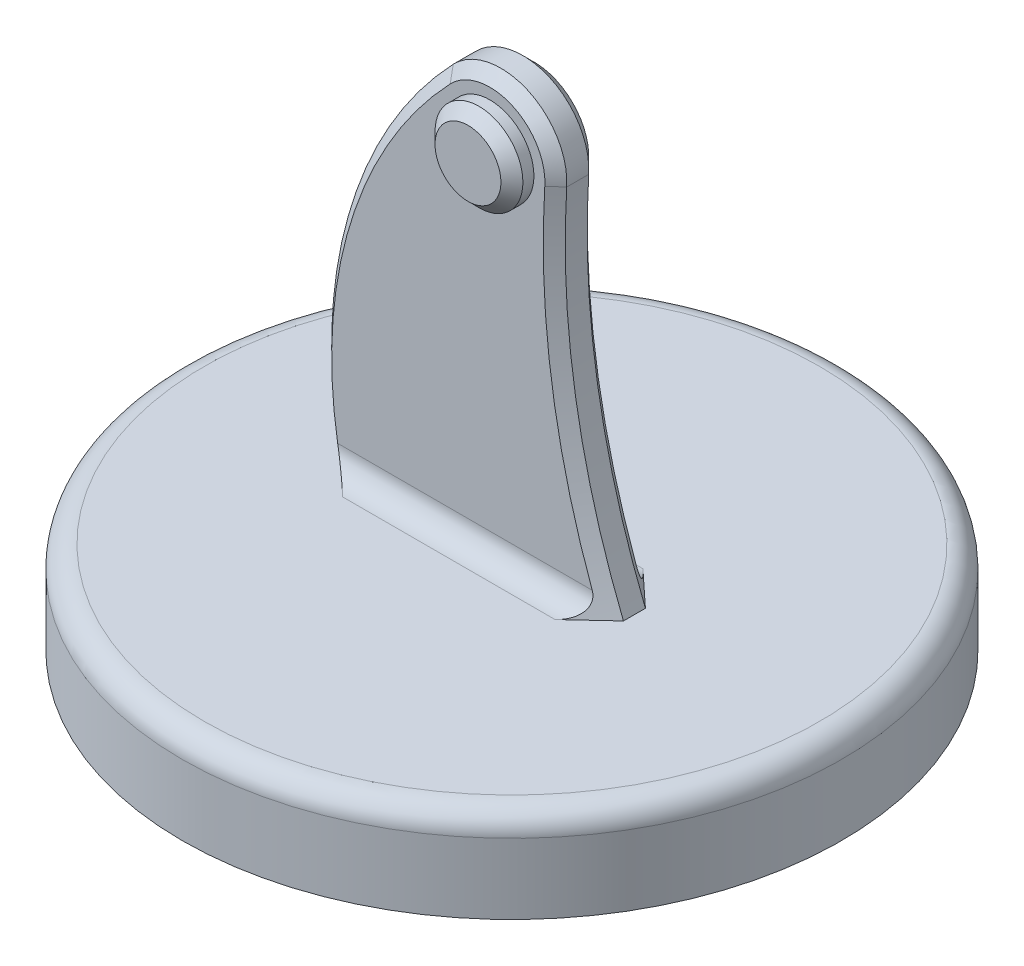
SolidWorks part; units mm, degrees
ref_plane "Front Plane" through (0, 0, 0) normal (0, 0, 1) x (1, 0, 0)
ref_plane "Top Plane" through (0, 0, 0) normal (0, 1, 0) x (1, 0, 0)
ref_plane "Right Plane" through (0, 0, 0) normal (1, 0, 0) x (0, 0, -1)
sketch "Sketch1" plane through (0, 0, 0) normal (0, 1, 0) x (1, 0, 0)
  circle A0 centre (0, 0) radius 75
  dimension "D1" = 150
extrude "Boss-Extrude1" add sketch "Sketch1" along normal blind 20 and the other way blind 1
fillet "Fillet1" radius 5 1 edges at (0, 20, 75)
sketch "Sketch3" plane through (0, 0, 0) normal (0, 0, 1) x (1, 0, 0)
  line L0 (0, 0) -> (0, 100) construction
  line L1 (-75, 15) -> (75, 15) construction
  line L2 (-35, 15) -> (30, 15)
  arc A0 (14.9706, 99.062) -> (-10.8492, 110.3583) centre (0, 100) ccw
  arc A1 (-35, 15) -> (-10.8492, 110.3583) centre (61.4788, 41.3028) cw
  arc A2 (14.9706, 99.062) -> (30, 15) centre (194.6184, 87.8065) ccw
  dimension "D1" = 30
  dimension "D3" = 180
  dimension "D6" = 100
  dimension "D2" = 100
  dimension "D4" = 30
  dimension "D5" = 35
extrude "Boss-Extrude2" add sketch "Sketch3" along normal mid plane 10
chamfer "Chamfer1" distance 2.5 angle 45 6 edges at (-34.7965, 68.3412, -5) (6.0123, 113.7423, -5) (16.9703, 58.8038, -5) (-34.7965, 68.3412, 5) (6.0123, 113.7423, 5) (16.9703, 58.8038, 5)
fillet "Fillet2" radius 5 2 edges at (-4.2415, 20, 5) (-4.2415, 20, -5)
sketch "Sketch4" plane through (0, 0, 5) normal (0, 0, 1) x (1, 0, 0)
  circle A0 centre (0, 100) radius 10
  dimension "D1" = 20
extrude "Boss-Extrude3" add sketch "Sketch4" along normal blind 5
chamfer "Chamfer2" distance 2.5 angle 45 1 edges at (10, 100, 10)
sketch "Sketch5" plane through (0, 0, -5) normal (0, 0, -1) x (-1, 0, 0)
  circle A0 centre (0, 100) radius 5
  dimension "D1" = 10
extrude "Cut-Extrude1" cut sketch "Sketch5" against normal blind 10
